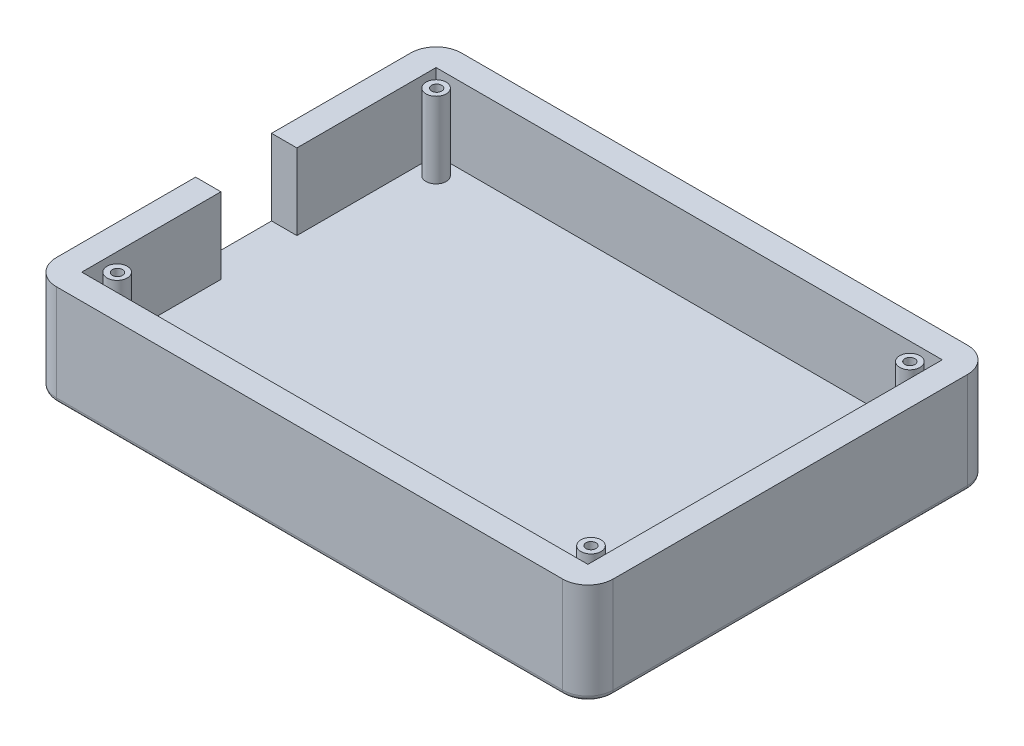
SolidWorks part; units mm, degrees
ref_plane "Front Plane" through (0, 0, 0) normal (0, 0, 1) x (1, 0, 0)
ref_plane "Top Plane" through (0, 0, 0) normal (0, 1, 0) x (1, 0, 0)
ref_plane "Right Plane" through (0, 0, 0) normal (1, 0, 0) x (0, 0, -1)
sketch "Sketch4" plane through (0, 0, 0) normal (0, 1, 0) x (1, 0, 0)
  line L1 (-55, -40) -> (55, -40)
  line L2 (-55, -40) -> (-55, 40)
  line L3 (-55, 40) -> (55, 40)
  line L4 (55, -40) -> (55, 40)
  line L5 (-55, -40) -> (55, 40) construction
  line L6 (-55, 40) -> (55, -40) construction
  point P0 (0, 0)
  dimension "D1" = 110
  dimension "D2" = 80
extrude "Boss-Extrude1" add sketch "Sketch4" along normal blind 20
shell "Shell1" thickness 5
fillet "Fillet1" radius 5 4 edges at (-55, 10, -40) (55, 10, -40) (55, 10, 40) (-55, 10, 40)
sketch "Sketch8" plane through (-55, 0, 0) normal (-1, 0, 0) x (0, 0, 1)
  line L0 (-35, 0) -> (35, 0) construction
  line L2 (-35, 10) -> (35, 10) construction
  line L3 (-35, 20) -> (-35, 0) construction
  line L4 (35, 0) -> (35, 20) construction
  line L6 (-7.5, 5) -> (7.5, 5)
  line L7 (-7.5, 5) -> (-7.5, 20)
  line L8 (-7.5, 20) -> (7.5, 20)
  line L9 (7.5, 5) -> (7.5, 20)
  line L10 (-7.5, 5) -> (7.5, 20) construction
  line L11 (-7.5, 20) -> (7.5, 5) construction
  point P11 (0, 12.5)
  dimension "D1" = 15
  dimension "D2" = 15
  dimension "D3" = 5
extrude "Cut-Extrude2" cut sketch "Sketch8" against normal up to surface (5 mm away) up to face at (-50, 12.5, 0)
sketch "Sketch10" plane through (0, 5, 0) normal (0, 1, 0) x (1, 0, 0)
  line L0 (50, 35) -> (-50, 35) construction
  line L1 (50, -35) -> (50, 35) construction
  line L2 (-55, 0) -> (50, 0) construction
  line L3 (-55, 7.5) -> (-55, -7.5) construction
  line L4 (-0.7171, 35) -> (0, -35) construction
  line L5 (50, 35) -> (-50, 35) construction
  line L6 (-50, -35) -> (50, -35) construction
  line L7 (-50, 35) -> (-50, 7.5) construction
  line L8 (50, 40) -> (-50, 40) construction
  line L9 (55, -35) -> (55, 35) construction
  line L10 (-55, 35) -> (-55, 7.5) construction
  line L11 (-50, -40) -> (50, -40) construction
  line L12 (-55, -7.5) -> (-55, -35) construction
  circle A0 centre (47.1, 31.5) radius 2
  circle A1 centre (47.1, -31.5) radius 2
  circle A2 centre (-46.5, 31.5) radius 2
  circle A3 centre (-46.5, -31.5) radius 2
  circle A4 centre (47.1, 31.5) radius 1
  circle A5 centre (47.1, -31.5) radius 1
  circle A6 centre (-46.4124, 31.5287) radius 1
  circle A7 centre (-46.4124, -31.5287) radius 1
  dimension "D1" = 4
  dimension "D2" = 3.5
  dimension "D4" = 4
  dimension "D5" = 3.5
  dimension "D6" = 3.5
  dimension "D7" = 8.5
  dimension "D13" = 8.5
  dimension "D8" = 7.9
  dimension "D9" = 8.5
  dimension "D10" = 8.5
  dimension "D11" = 8.5
  dimension "D12" = 8.5
  dimension "D14" = 7.9
  dimension "D15" = 8.5
extrude "Boss-Extrude2" add sketch "Sketch10" along normal up to surface (15 mm away) contours A2 | A1 | A3 | A0
fillet "Fillet2" radius 1 8 edges at (53.5355, 0, 38.5355) (0, 0, 40) (-53.5355, 0, 38.5355) (-55, 0, 0) (-53.5355, 0, -38.5355) (0, 0, -40) (53.5355, 0, -38.5355) (55, 0, 0)
